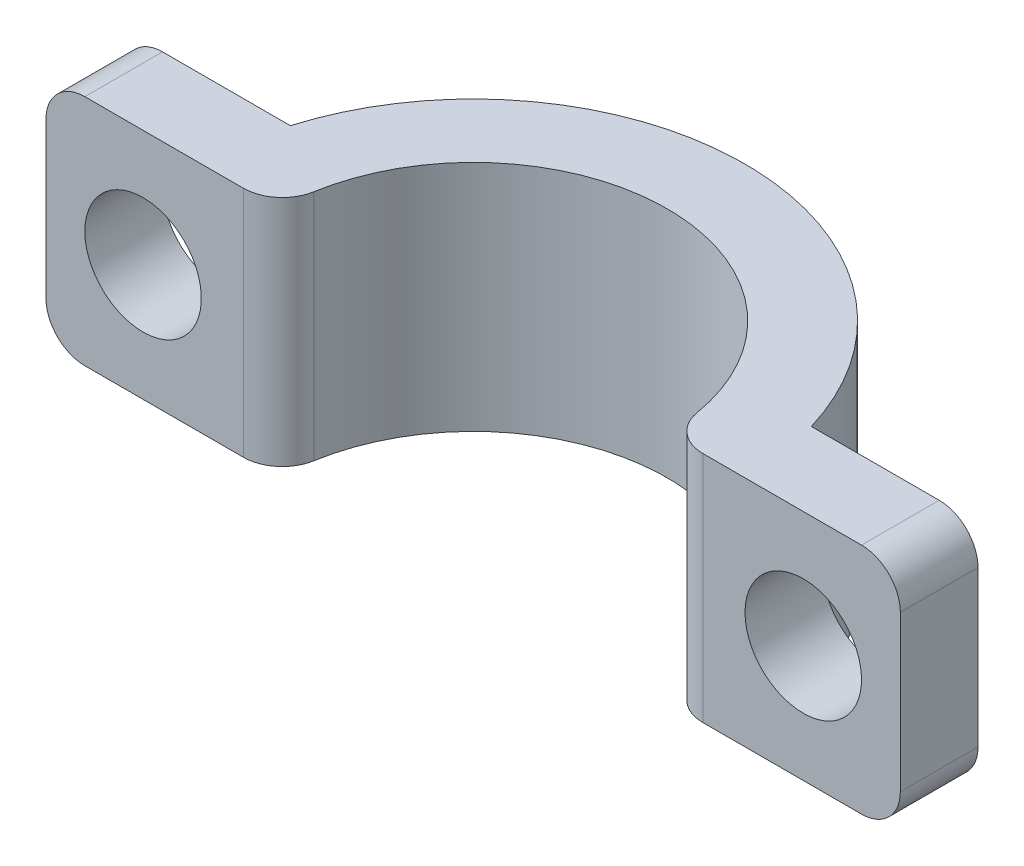
SolidWorks part; units mm, degrees
ref_plane "Front Plane" through (0, 0, 0) normal (0, 0, 1) x (1, 0, 0)
ref_plane "Top Plane" through (0, 0, 0) normal (0, 1, 0) x (1, 0, 0)
ref_plane "Right Plane" through (0, 0, 0) normal (1, 0, 0) x (0, 0, -1)
sketch "Sketch1" plane through (0, 0, 0) normal (0, 1, 0) x (1, 0, 0)
  line L0 (5, 0) -> (7, 0)
  line L1 (-5, 0) -> (-7, 0)
  arc A0 (5, 0) -> (-5, 0) centre (0, 0) ccw
  arc A1 (7, 0) -> (-7, 0) centre (0, 0) ccw
  dimension "D1" = 10
  dimension "D2" = 14
extrude "Boss-Extrude1" add sketch "Sketch1" along normal blind 6
sketch "Sketch2" plane through (0, 6, 0) normal (0, 1, 0) x (1, 0, 0)
  line L0 (7, 0) -> (11, 0)
  line L1 (11, 0) -> (11, 2)
  line L2 (11, 2) -> (6.7082, 2)
  line L3 (6.7082, 2) -> (7, 0)
  line L4 (0, -3.3) -> (0, 3.3) construction
  line L5 (-6.7082, 2) -> (-7, 0)
  line L6 (-11, 2) -> (-6.7082, 2)
  line L7 (-11, 0) -> (-11, 2)
  line L8 (-7, 0) -> (-11, 0)
  arc A0 (7, 0) -> (-7, 0) centre (0, 0) ccw construction
  dimension "D1" = 4
  dimension "D2" = 2
extrude "Boss-Extrude2" add sketch "Sketch2" against normal up to surface (6 mm away) up to face at (0, 0, -3)
sketch "Sketch3" plane through (0, 0, -2) normal (0, 0, -1) x (-1, 0, 0)
  line L0 (-11, 3) -> (-8.5, 3) construction
  line L1 (-11, 0) -> (-11, 6) construction
  line L2 (0, 3.3) -> (0, -3.3) construction
  circle A0 centre (-8.5, 3) radius 1.5
  circle A1 centre (8.5, 3) radius 1.5
  dimension "D2" = 3
  dimension "D1" = 2.5
extrude "Cut-Extrude1" cut sketch "Sketch3" against normal blind 6
fillet "Fillet1" radius 1 6 edges at (5, 3, 0) (-5, 3, 0) (-11, 0, -1) (11, 0, -1) (11, 6, -1) (-11, 6, -1)
